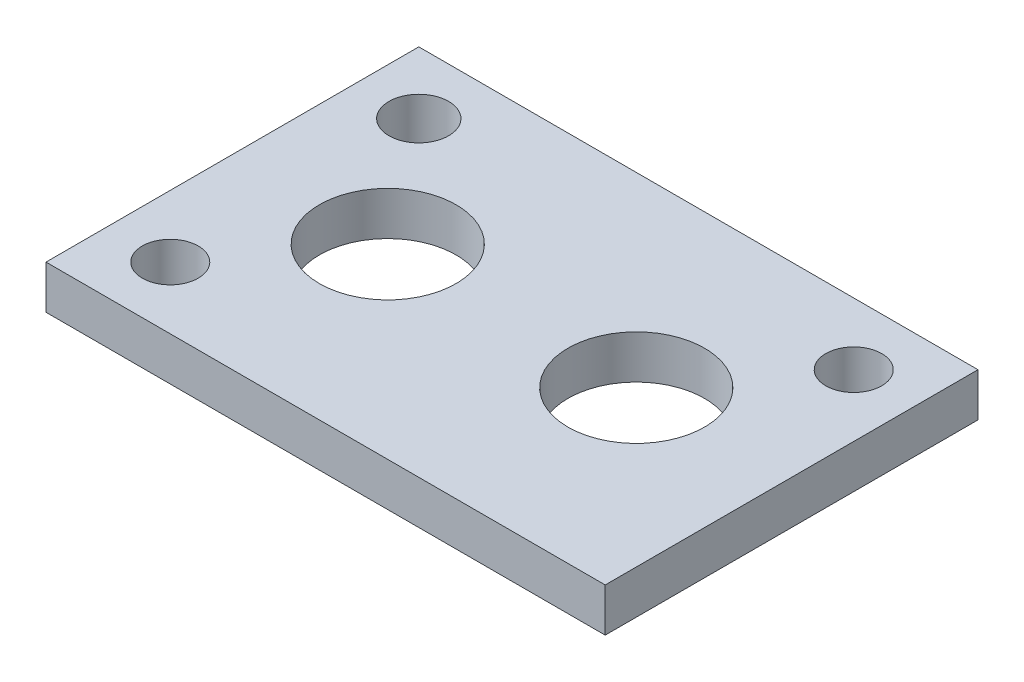
SolidWorks part; units mm, degrees
ref_plane "Front Plane" through (0, 0, 0) normal (0, 0, 1) x (1, 0, 0)
ref_plane "Top Plane" through (0, 0, 0) normal (0, 1, 0) x (1, 0, 0)
ref_plane "Right Plane" through (0, 0, 0) normal (1, 0, 0) x (0, 0, -1)
sketch "Sketch1" plane through (0, 0, 0) normal (0, 1, 0) x (1, 0, 0)
  line L1 (0, 0) -> (90, 0)
  line L2 (0, 0) -> (0, 60)
  line L3 (0, 60) -> (90, 60)
  line L4 (90, 0) -> (90, 60)
  dimension "D1" = 60
  dimension "D2" = 90
extrude "Boss-Extrude1" add sketch "Sketch1" along normal blind 7
hole_wizard "M20 Clearance Slot1" positions "Sketch2" profile "Sketch3" size "M20" standard "ANSI Metric" slot yes end condition through all
sketch "Sketch2" plane through (0, 7, 0) normal (0, 1, 0) x (1, 0, 0)
  line L1 (0, 60) -> (0, 0) construction
  line L2 (90, 60) -> (0, 60) construction
  line L3 (90, 0) -> (90, 60) construction
  point P0 (25, 30)
  point P2 (65, 30)
  point P9 (0, 30)
  dimension "D1" = 25
  dimension "D2" = 30
  dimension "D3" = 30
  dimension "D4" = 25
  dimension "D5" = 40
sketch "Sketch3" plane through (25, 7, -30) normal (1, 0, 0) x (0, 0, 1)
  line L0 (0, 0) -> (0, 7)
  line L1 (0, 7) -> (11, 7)
  line L2 (11, 7) -> (11, 0)
  line L5 (11, 0) -> (0, 0)
  line L11 (0, -6.35) -> (0, 107.95) construction
  dimension "Thru Hole Dia." = 22
  dimension "Thru Hole Depth" = 7
hole_wizard "M8 Clearance Slot1" positions "Sketch4" profile "Sketch5" size "M8" standard "ANSI Metric" slot yes end condition through all
sketch "Sketch4" plane through (0, 7, 0) normal (0, 1, 0) x (1, 0, 0)
  line L1 (90, 60) -> (0, 60) construction
  line L2 (0, 0) -> (90, 0) construction
  line L3 (90, 0) -> (90, 60) construction
  line L4 (0, 60) -> (0, 0) construction
  point P0 (80, 50)
  point P2 (10, 10)
  dimension "D1" = 10
  dimension "D2" = 10
  dimension "D3" = 10
  dimension "D4" = 10
sketch "Sketch5" plane through (80, 7, -50) normal (1, 0, 0) x (0, 0, 1)
  line L0 (0, 0) -> (0, 7)
  line L1 (0, 7) -> (4.5, 7)
  line L2 (4.5, 7) -> (4.5, 0)
  line L5 (4.5, 0) -> (0, 0)
  line L11 (0, -6.35) -> (0, 107.95) construction
  dimension "Thru Hole Dia." = 9
  dimension "Thru Hole Depth" = 7
sketch "Sketch8" plane through (0, 7, 0) normal (0, 1, 0) x (1, 0, 0)
  line L0 (90, 60) -> (0, 60) construction
  line L1 (0, 60) -> (0, 0) construction
  circle A0 centre (10, 50) radius 4.8
  dimension "D1" = 10
  dimension "D2" = 10
extrude "Cut-Extrude1" cut sketch "Sketch8" against normal blind 7
